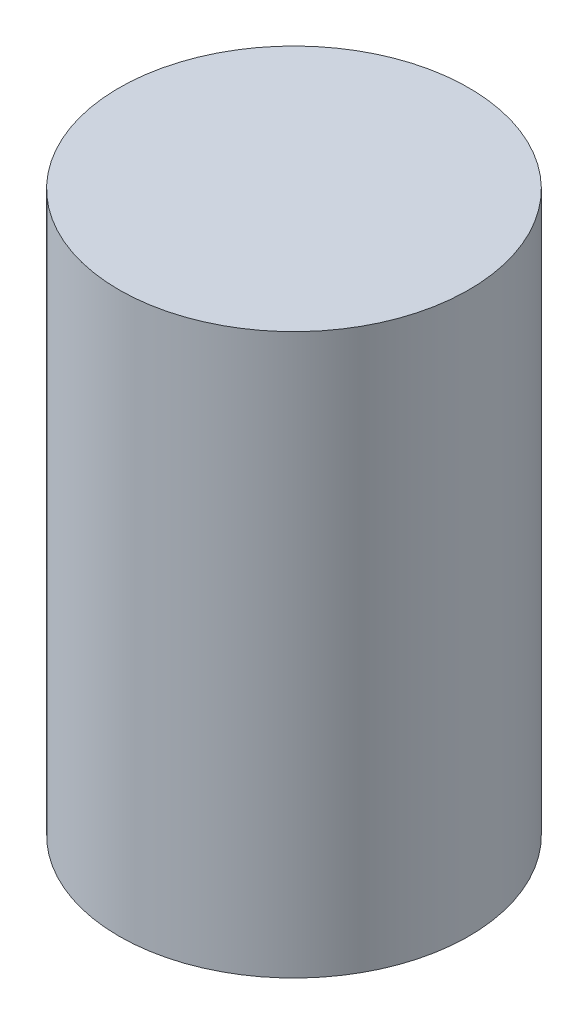
SolidWorks part; units mm, degrees
ref_plane "Front Plane" through (0, 0, 0) normal (0, 0, 1) x (1, 0, 0)
ref_plane "Top Plane" through (0, 0, 0) normal (0, 1, 0) x (1, 0, 0)
ref_plane "Right Plane" through (0, 0, 0) normal (1, 0, 0) x (0, 0, -1)
sketch "Sketch1" plane through (0, 0, 0) normal (0, 1, 0) x (1, 0, 0)
  circle A0 centre (0, 0) radius 250
  dimension "D1" = 500
extrude "Boss-Extrude1" add sketch "Sketch1" along normal blind 800
